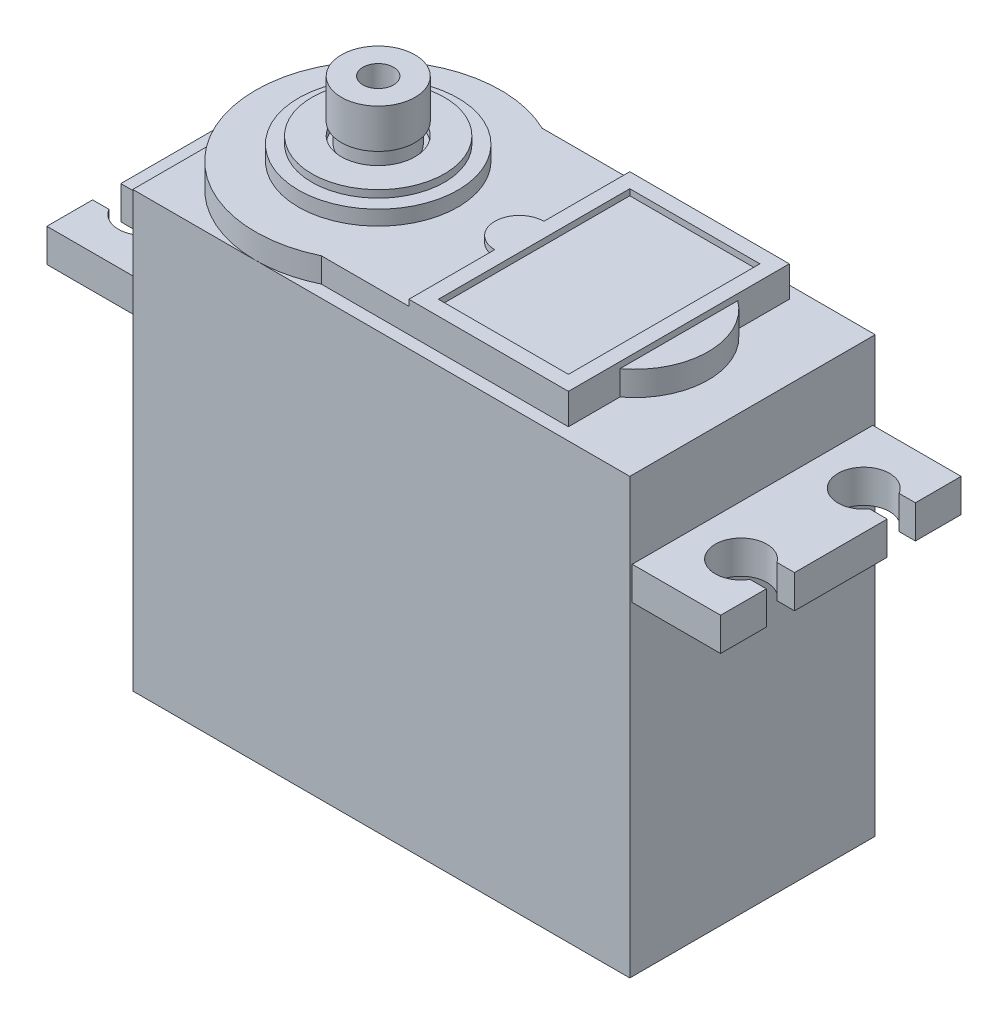
SolidWorks part; units mm, degrees
ref_plane "Front Plane" through (0, 0, 0) normal (0, 0, 1) x (1, 0, 0)
ref_plane "Top Plane" through (0, 0, 0) normal (0, 1, 0) x (1, 0, 0)
ref_plane "Right Plane" through (0, 0, 0) normal (1, 0, 0) x (0, 0, -1)
sketch "Sketch1" plane through (0, 0, 0) normal (0, 1, 0) x (1, 0, 0)
  line L1 (-20.25, -10) -> (20.25, -10)
  line L2 (-20.25, -10) -> (-20.25, 10)
  line L3 (-20.25, 10) -> (20.25, 10)
  line L4 (20.25, -10) -> (20.25, 10)
  line L5 (-20.25, -10) -> (20.25, 10) construction
  line L6 (-20.25, 10) -> (20.25, -10) construction
  point P0 (0, 0)
  dimension "D1" = 40.5
  dimension "D2" = 20
extrude "Boss-Extrude1" add sketch "Sketch1" along normal blind 37 contours L3 L4 L1 L2
sketch "Sketch2" plane through (-20.25, 0, 0) normal (-1, 0, 0) x (0, 0, 1)
  line L1 (-9.8, 28) -> (9.8, 28)
  line L2 (-9.8, 28) -> (-9.8, 30.7)
  line L3 (-9.8, 30.7) -> (9.8, 30.7)
  line L4 (9.8, 28) -> (9.8, 30.7)
  line L6 (10, 37) -> (-10, 37) construction
  line L7 (0, 0) -> (0, 50000) construction
  line L8 (10, 0) -> (-10, 0) construction
  line L9 (10, 37) -> (10, 0) construction
  line L10 (-10, 37) -> (-10, 0) construction
  point P6 (-9.8, 29.35)
  point P14 (0, 0)
  dimension "D1" = 9
  dimension "D2" = 2.7
  dimension "D3" = 0.2
  dimension "D4" = 0.2
extrude "Boss-Extrude2" add sketch "Sketch2" along normal blind 7.2
sketch "Sketch3" plane through (0, 30.7, 0) normal (0, 1, 0) x (1, 0, 0)
  line L2 (-27.45, -3.7755) -> (-27.45, -6.0733)
  line L3 (-26.0221, -3.7755) -> (-27.45, -3.7755)
  line L4 (-27.45, -9.8) -> (-27.45, 9.8) construction
  line L5 (-26.1211, -6.0733) -> (-27.45, -6.0733)
  line L6 (-20.25, 0) -> (-27.45, 0) construction
  line L7 (-20.25, -9.8) -> (-20.25, 9.8) construction
  line L8 (-26.1211, 6.0733) -> (-27.45, 6.0733)
  line L9 (-26.0221, 3.7755) -> (-27.45, 3.7755)
  line L10 (-27.45, 3.7755) -> (-27.45, 6.0733)
  arc A0 (-26.1211, -6.0733) -> (-26.0221, -3.7755) centre (-24.3161, -5) ccw
  arc A1 (-26.1211, 6.0733) -> (-26.0221, 3.7755) centre (-24.3161, 5) cw
  point P2 (-24.3161, -2.9)
  point P4 (-24.3161, -7.1)
  point P19 (-24.3161, 7.1)
  dimension "D1" = 4.2
  dimension "D2" = 2.9
  dimension "D3" = 2.3
extrude "Cut-Extrude1" cut sketch "Sketch3" against normal through all
mirror "Mirror2" about plane through (0, 0, 0) normal (1, 0, 0) of "Cut-Extrude1", "Boss-Extrude2"
sketch "Sketch5" plane through (0, 37, 0) normal (0, 1, 0) x (1, 0, 0)
  line L0 (-20.25, 10) -> (20.25, 10) construction
  line L3 (-20.25, -10) -> (-20.25, 10) construction
  line L4 (-20.25, -10) -> (20.25, -10) construction
  line L5 (-10.25, 0) -> (49989.75, 0) construction
  line L6 (20.25, -10) -> (20.25, 10) construction
  line L7 (-5.8911, -9) -> (14.25, -9)
  line L9 (-5.8911, 9) -> (14.25, 9)
  line L10 (14.25, -9) -> (14.25, -4.8)
  line L11 (-5.8911, -9) -> (14.25, 9) construction
  line L12 (-5.8911, 9) -> (14.25, -9) construction
  line L13 (14.25, 4.8) -> (14.25, 9)
  arc A0 (-5.8911, 9) -> (-5.8911, -9) centre (-10.25, 0) ccw
  arc A2 (14.25, -4.8) -> (14.25, 4.8) centre (10.65, 0) ccw
  point P8 (4.1794, 0)
  point P15 (16.65, 0)
  dimension "D1" = 18
  dimension "D3" = 3.6
  dimension "D2" = 6
extrude "Boss-Extrude3" add sketch "Sketch5" along normal blind 2
sketch "Sketch6" plane through (0, 39, 0) normal (0, 1, 0) x (1, 0, 0)
  circle A0 centre (-10.25, 0) radius 6.5
  dimension "D1" = 13
extrude "Boss-Extrude4" add sketch "Sketch6" along normal blind 1.2
sketch "Sketch7" plane through (0, 40.2, 0) normal (0, 1, 0) x (1, 0, 0)
  circle A0 centre (-10.25, 0) radius 5.4
  dimension "D1" = 10.8
extrude "Boss-Extrude5" add sketch "Sketch7" along normal blind 0.6
sketch "Sketch8" plane through (0, 40.8, 0) normal (0, 1, 0) x (1, 0, 0)
  circle A0 centre (-10.25, 0) radius 3
  circle A1 centre (-10.25, 0) radius 2.6
extrude "Cut-Extrude2" cut sketch "Sketch8" against normal blind 0.6
sketch "Sketch9" plane through (0, 40.8, 0) normal (0, 1, 0) x (1, 0, 0)
  circle A0 centre (-10.25, 0) radius 2.6
extrude "Boss-Extrude6" add sketch "Sketch9" along normal blind 1
sketch "Sketch10" plane through (0, 41.8, 0) normal (0, 1, 0) x (1, 0, 0)
  circle A0 centre (-10.25, 0) radius 3
extrude "Boss-Extrude7" add sketch "Sketch10" along normal blind 3.2
sketch "Sketch11" plane through (0, 45, 0) normal (0, 1, 0) x (1, 0, 0)
  circle A0 centre (-10.25, 0) radius 1.25
extrude "Cut-Extrude3" cut sketch "Sketch11" against normal blind 10
sketch "Sketch12" plane through (0, 39, 0) normal (0, 1, 0) x (1, 0, 0)
  line L0 (-5.8911, -9) -> (14.25, -9) construction
  line L1 (14.25, 9) -> (1.25, 9)
  line L2 (14.25, 9) -> (14.25, -9)
  line L3 (14.25, -9) -> (1.25, -9)
  line L4 (1.25, 9) -> (1.25, 2)
  line L5 (13.05, 7.8) -> (2.45, 7.8)
  line L6 (2.45, 7.8) -> (2.45, -7.8)
  line L7 (13.05, -7.8) -> (2.45, -7.8)
  line L8 (13.05, 7.8) -> (13.05, -7.8)
  line L9 (1.25, 9) -> (1.25, -9) construction
  line L10 (1.25, -2) -> (1.25, -9)
  arc A0 (1.25, 2) -> (1.25, -2) centre (1.25, 0) ccw
  dimension "D1" = 13
  dimension "D2" = 1.2
extrude "Boss-Extrude8" add sketch "Sketch12" along normal blind 0.5
chamfer "Chamfer1" distance 1.6 angle 45 4 edges at (0, 0, 10) (20.25, 0, 0) (0, 0, -10) (-20.25, 0, 0)
sketch "Sketch13" plane through (-20.25, 0, 0) normal (-1, 0, 0) x (0, 0, 1)
  line L0 (0, 0) -> (0, 50000) construction
  line L1 (8.4, 0) -> (-8.4, 0) construction
  line L2 (-3.5, 3.7) -> (3.5, 3.7)
  line L3 (-3.5, 3.7) -> (-3.5, 7.7)
  line L4 (-3.5, 7.7) -> (3.5, 7.7)
  line L5 (3.5, 3.7) -> (3.5, 7.7)
  line L6 (-3.5, 3.7) -> (3.5, 7.7) construction
  line L7 (-3.5, 7.7) -> (3.5, 3.7) construction
  point P3 (0, 5.7)
  dimension "D1" = 7
  dimension "D2" = 4
  dimension "D3" = 7.7
extrude "Boss-Extrude9" add sketch "Sketch13" along normal blind 5.2
draft "Draft1" type of draft neutral plane draft angle 10 faces to draft 4 face at (-22.85, 7.7, 0) face at (-22.85, 5.7, 3.5) face at (-22.85, 5.7, -3.5) face at (-22.85, 3.7, 0) neutral plane through (-20.25, 37, 10) neutral plane normal (-1, 0, 0) parameters "D1"=10
